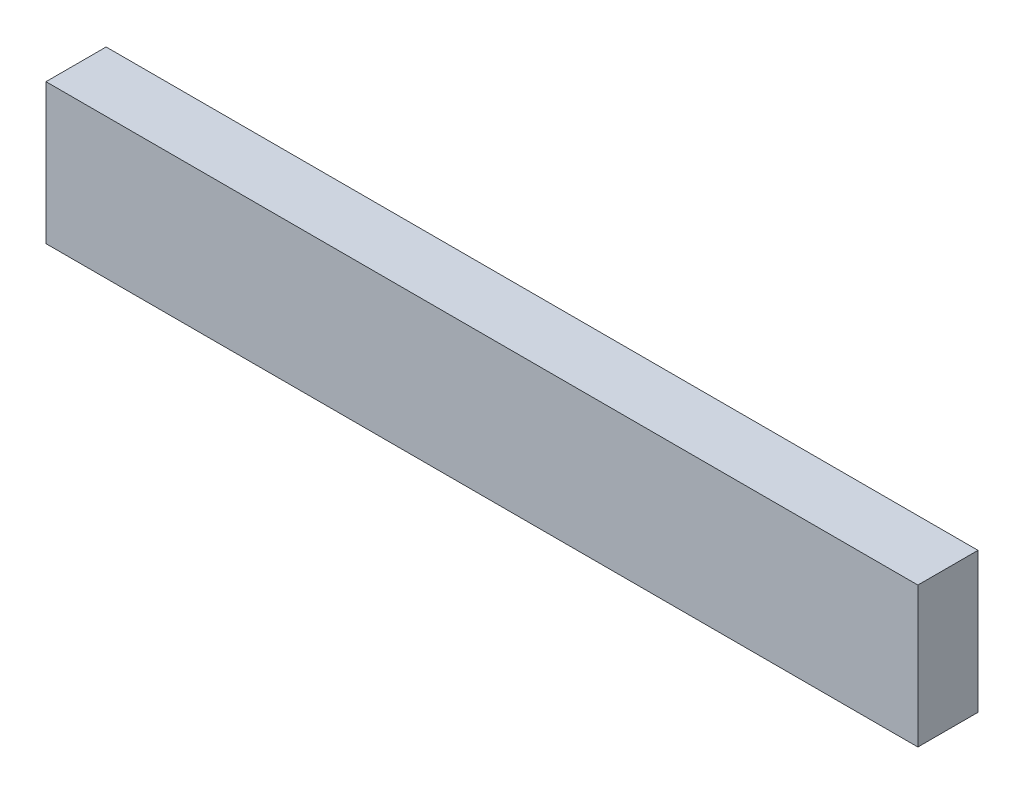
SolidWorks part; units mm, degrees
material "Pine"
ref_plane "Front Plane" through (0, 0, 0) normal (0, 0, 1) x (1, 0, 0)
ref_plane "Top Plane" through (0, 0, 0) normal (0, 1, 0) x (1, 0, 0)
ref_plane "Right Plane" through (0, 0, 0) normal (1, 0, 0) x (0, 0, -1)
sketch "Sketch1" plane through (0, 0, 0) normal (1, 0, 0) x (0, 0, -1)
  line L1 (0, 0) -> (38.1, 0)
  line L2 (0, 0) -> (0, 88.9)
  line L3 (0, 88.9) -> (38.1, 88.9)
  line L4 (38.1, 0) -> (38.1, 88.9)
  dimension "D1" = 38.1
  dimension "D2" = 88.9
extrude "Boss-Extrude1" add sketch "Sketch1" along normal blind 552.45
